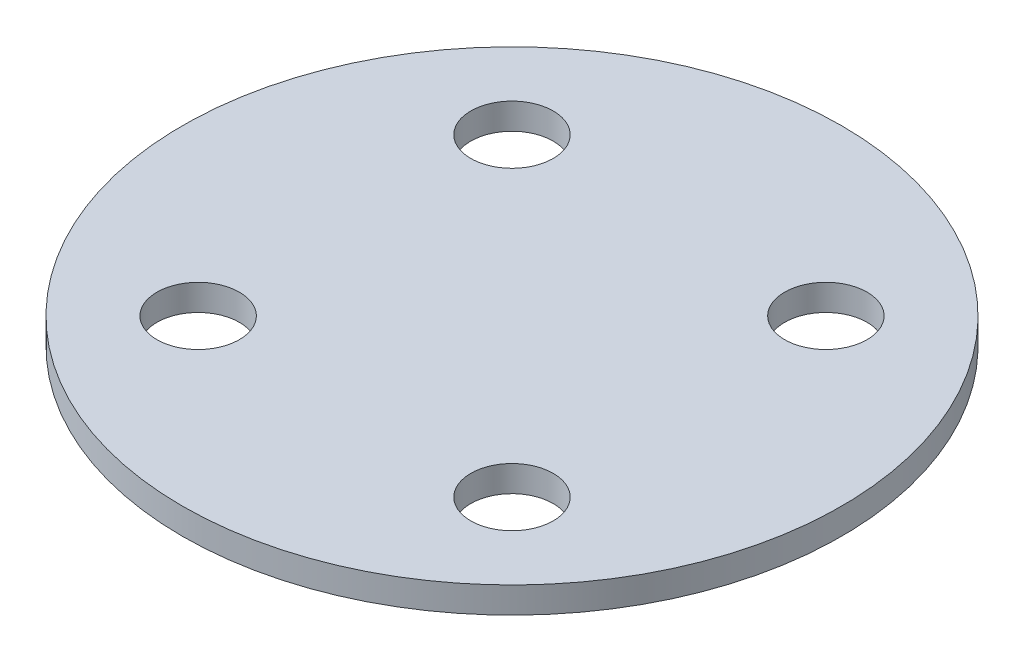
SolidWorks part; units mm, degrees
material "ABS"
ref_plane "Front Plane" through (0, 0, 0) normal (0, 0, 1) x (1, 0, 0)
ref_plane "Top Plane" through (0, 0, 0) normal (0, 1, 0) x (1, 0, 0)
ref_plane "Right Plane" through (0, 0, 0) normal (1, 0, 0) x (0, 0, -1)
sketch "Sketch1" plane through (0, 85.0801, 0) normal (0, -1, 0) x (1, 0, 0)
  circle A0 centre (-89.0728, -47.2587) radius 12.6
  circle A1 centre (-95.0728, -41.2587) radius 1.575
  circle A2 centre (-83.0728, -41.2587) radius 1.575
  circle A3 centre (-83.0728, -53.2587) radius 1.575
  circle A4 centre (-95.0728, -53.2587) radius 1.575
  point P6 (0, 0)
  point P7 (0, 0)
  point P8 (0, 0)
  point P15 (-89.0728, -47.2587)
  point P16 (0, 0)
  point P17 (0, 0)
  point P18 (0, 0)
  point P19 (0, 0)
  point P20 (0, 0)
  point P21 (0, 0)
  point P22 (0, 0)
  point P23 (0, 0)
  point P24 (0, 0)
  point P25 (-89.0728, -47.2587)
  dimension "D1" = 25.2
  dimension "D2" = 3.15
  dimension "D3" = 4
extrude "Boss-Extrude1" add sketch "Sketch1" along normal blind 1
